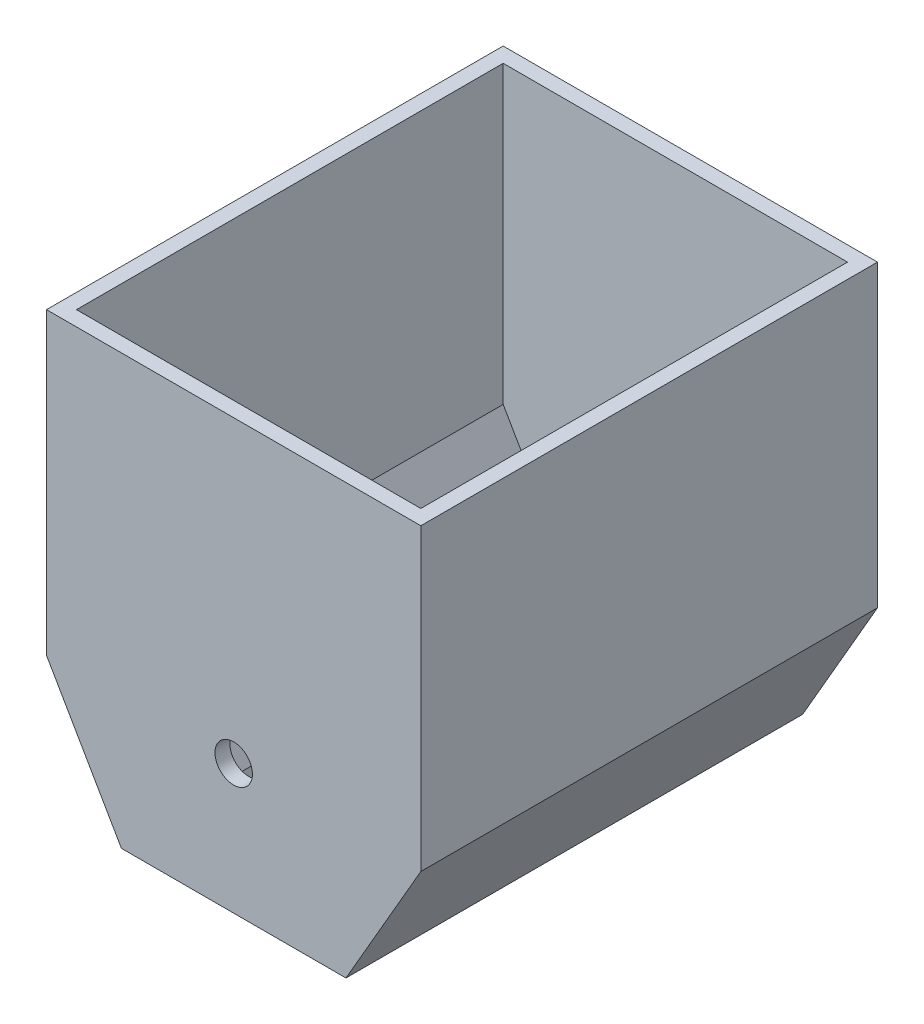
SolidWorks part; units mm, degrees
ref_plane "Front Plane" through (0, 0, 0) normal (0, 0, 1) x (1, 0, 0)
ref_plane "Top Plane" through (0, 0, 0) normal (0, 1, 0) x (1, 0, 0)
ref_plane "Right Plane" through (0, 0, 0) normal (1, 0, 0) x (0, 0, -1)
sketch "Sketch1" plane through (0, 0, 0) normal (0, 0, 1) x (1, 0, 0)
  line L0 (-19.05, 0) -> (19.05, 0)
  line L1 (55, 0) -> (-55, 0) construction
  line L2 (19.05, 0) -> (31.75, 21.997)
  line L3 (31.75, 21.997) -> (31.75, 72.797)
  line L4 (31.75, 72.797) -> (-31.75, 72.797)
  line L5 (-31.75, 72.797) -> (-31.75, 21.997)
  line L6 (-31.75, 21.997) -> (-19.05, 0)
  point P6 (0, 0)
  dimension "D1" = 63.5
  dimension "D2" = 50.8
  dimension "D3" = 150
  dimension "D4" = 25.4
  dimension "D5" = 120
extrude "Boss-Extrude1" add sketch "Sketch1" along normal mid plane 77.47
shell "Shell1" thickness 2.54
sketch "Sketch4" plane through (0, 2.54, 0) normal (0, 1, 0) x (1, 0, 0)
  line L1 (-17.5835, 36.195) -> (17.5835, 36.195)
  line L2 (-17.5835, 36.195) -> (-17.5835, -36.195)
  line L3 (-17.5835, -36.195) -> (17.5835, -36.195)
  line L4 (17.5835, 36.195) -> (17.5835, -36.195)
  line L5 (-17.5835, 36.195) -> (17.5835, -36.195) construction
  line L6 (-17.5835, -36.195) -> (17.5835, 36.195) construction
  point P0 (0, 0)
extrude "Cut-Extrude1" cut sketch "Sketch4" against normal through all
sketch "Sketch6" plane through (0, 0, 38.735) normal (0, 0, 1) x (1, 0, 0)
  line L0 (-31.75, 21.997) -> (31.75, 21.997) construction
  circle A0 centre (0, 21.997) radius 3.175
  point P4 (0, 21.997)
  dimension "D1" = 6.35
extrude "Cut-Extrude2" cut sketch "Sketch6" against normal through all and the other way through all
